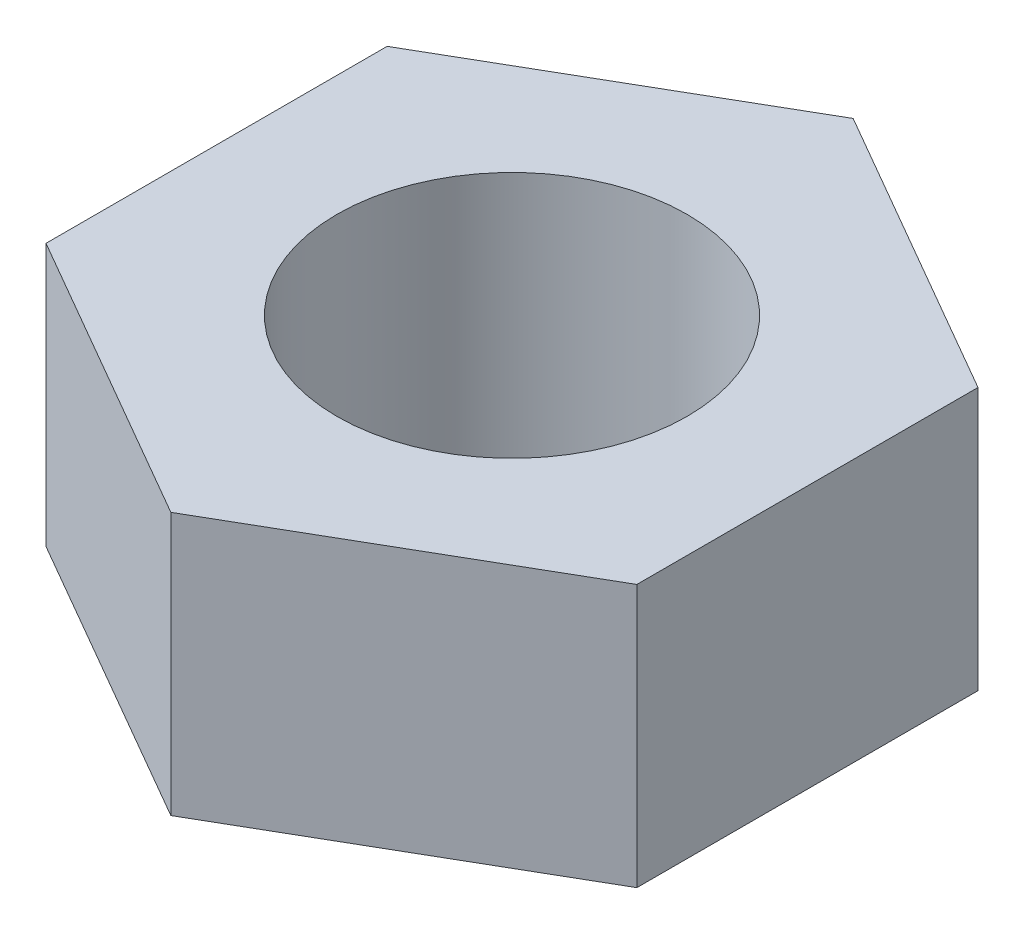
SolidWorks part; units mm, degrees
ref_plane "Front Plane" through (0, 0, 0) normal (0, 0, 1) x (1, 0, 0)
ref_plane "Top Plane" through (0, 0, 0) normal (0, 1, 0) x (1, 0, 0)
ref_plane "Right Plane" through (0, 0, 0) normal (1, 0, 0) x (0, 0, -1)
sketch "Sketch1" plane through (0, 0, 0) normal (0, 1, 0) x (1, 0, 0)
  line L1 (0, 7.7942) -> (-6.75, 3.8971)
  line L2 (-6.75, 3.8971) -> (-6.75, -3.8971)
  line L3 (-6.75, -3.8971) -> (0, -7.7942)
  line L4 (0, -7.7942) -> (6.75, -3.8971)
  line L5 (6.75, -3.8971) -> (6.75, 3.8971)
  line L6 (6.75, 3.8971) -> (0, 7.7942)
  circle A0 centre (0, 0) radius 6.75 construction
  circle A1 centre (0, 0) radius 4
  dimension "D2" = 8
  dimension "D1" = 13.5
extrude "Boss-Extrude1" add sketch "Sketch1" along normal blind 6
